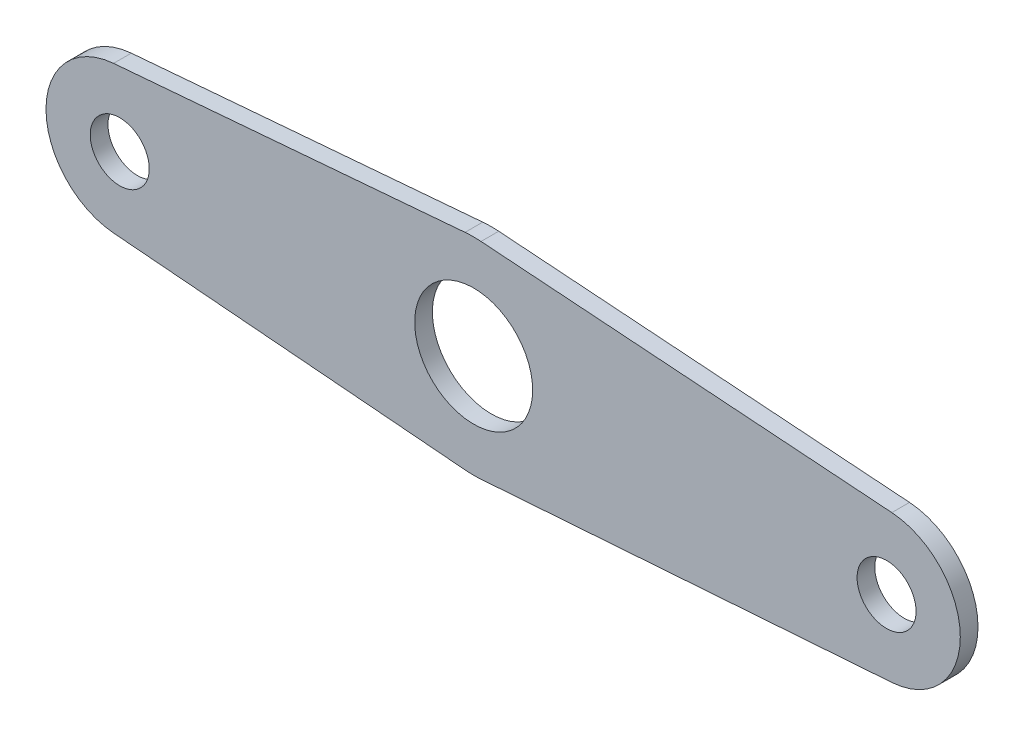
SolidWorks part; units mm, degrees
ref_plane "Piano frontale" through (0, 0, 0) normal (0, 0, 1) x (1, 0, 0)
ref_plane "Piano superiore" through (0, 0, 0) normal (0, 1, 0) x (1, 0, 0)
ref_plane "Piano destro" through (0, 0, 0) normal (1, 0, 0) x (0, 0, -1)
sketch "Schizzo1" plane through (0, 0, 0) normal (0, 0, 1) x (1, 0, 0)
  line L0 (-61.0417, 12.4565) -> (-1.4583, 17.4391)
  line L1 (1.25, 17.4553) -> (70.8929, 12.4681)
  line L2 (-61.0417, -12.4565) -> (-1.4583, -17.4391)
  line L3 (1.25, -17.4553) -> (70.8929, -12.4681)
  arc A0 (-1.4583, -17.4391) -> (1.25, -17.4553) centre (0, 0) ccw
  arc A1 (70.8929, -12.4681) -> (70.8929, 12.4681) centre (70, 0) ccw
  arc A2 (-61.0417, 12.4565) -> (-61.0417, -12.4565) centre (-60, 0) ccw
  arc A3 (1.25, 17.4553) -> (-1.4583, 17.4391) centre (0, 0) ccw
  circle A4 centre (-60, 0) radius 5
  circle A5 centre (0, 0) radius 10
  circle A6 centre (70, 0) radius 5
  dimension "D1" = 35
  dimension "D2" = 25
  dimension "D3" = 25
  dimension "D6" = 10
  dimension "D7" = 10
  dimension "D8" = 20
  dimension "D4" = 60
  dimension "D5" = 130
extrude "Estrusione-Estrusione1" add sketch "Schizzo1" along normal blind 3
